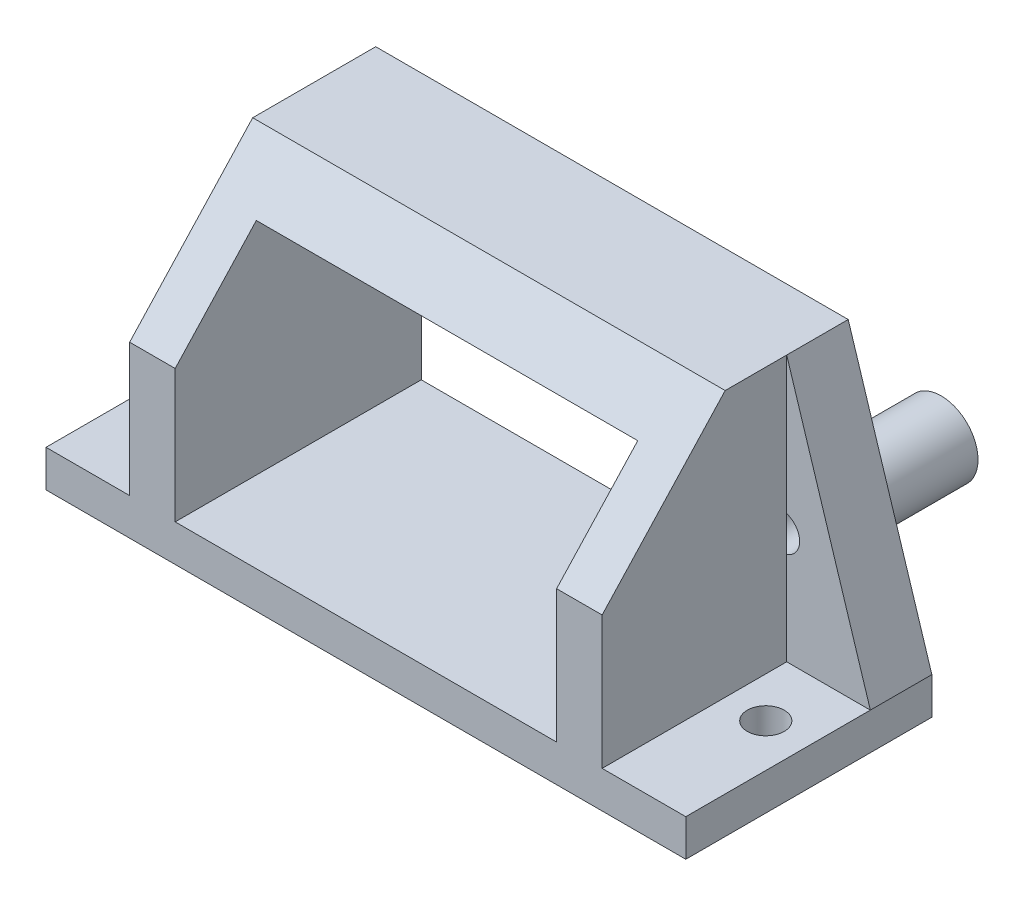
SolidWorks part; units mm, degrees
ref_plane "Front" through (0, 0, 0) normal (0, 0, 1) x (1, 0, 0)
ref_plane "Top" through (0, 0, 0) normal (0, 1, 0) x (1, 0, 0)
ref_plane "Right" through (0, 0, 0) normal (1, 0, 0) x (0, 0, -1)
sketch "草图1" plane through (0, 0, 0) normal (0, 0, 1) x (1, 0, 0)
  line L0 (-26, 0) -> (26, 0)
  line L1 (26, 0) -> (26, 3)
  line L2 (19.2013, 24.596) -> (-19.2013, 24.596)
  line L3 (-26, 3) -> (-26, 0)
  line L4 (-15.5, 3) -> (-15.5, 20.9193)
  line L5 (-15.5, 20.9193) -> (15.5, 20.9193)
  line L6 (15.5, 20.9193) -> (15.5, 3)
  line L7 (-15.5, 3) -> (15.5, 3)
  line L9 (19.2013, 24.596) -> (26, 3)
  line L10 (-26, 3) -> (-19.2013, 24.596)
extrude "凸台-拉伸1" add sketch "草图1" along normal blind 20
sketch "草图2" plane through (-15.5, 0, 0) normal (1, 0, 0) x (0, 0, -1)
  line L0 (-20, 13.798) -> (-10, 24.596)
  line L1 (-20, 3) -> (-20, 24.596) construction
  line L2 (-20, 24.596) -> (0, 24.596) construction
  line L3 (-10, 24.596) -> (-20, 24.596)
  line L4 (-20, 24.596) -> (-20, 13.798)
extrude "切除-拉伸1" cut sketch "草图2" against normal mid plane 92
sketch "草图3" plane through (0, 0, 20) normal (0, 0, 1) x (1, 0, 0)
  line L0 (19.2013, 24.596) -> (19.2013, 3)
  line L1 (19.2013, 3) -> (26, 3)
  line L2 (26, 3) -> (22.6006, 13.798) construction
  line L3 (26, 3) -> (19.2013, 24.596)
  line L4 (-19.2013, 24.596) -> (-26, 3)
  line L5 (-26, 3) -> (-19.2013, 3)
  line L6 (-19.2013, 3) -> (-19.2013, 24.596)
extrude "切除-拉伸2" cut sketch "草图3" against normal blind 15
sketch "草图4" plane through (0, 0, 0) normal (0, -1, 0) x (1, 0, 0)
  circle A1 centre (-22.5, 10) radius 1.5
  circle A2 centre (22.5, 10) radius 1.5
extrude "切除-拉伸3" cut sketch "草图4" against normal blind 15
sketch "草图5" plane through (0, 0, 5) normal (0, 0, 1) x (1, 0, 0)
  circle A1 centre (-18.75, 12) radius 1.5
  circle A2 centre (18.75, 12) radius 1.5
extrude "切除-拉伸4" cut sketch "草图5" against normal blind 10
sketch "草图6" plane through (0, 0, 0) normal (0, 0, -1) x (-1, 0, 0)
  circle A0 centre (18.75, 12) radius 1.5
  circle A1 centre (18.75, 12) radius 3
  circle A2 centre (-18.75, 12) radius 1.5
  circle A3 centre (-18.75, 12) radius 3
extrude "凸台-拉伸2" add sketch "草图6" along normal blind 8
